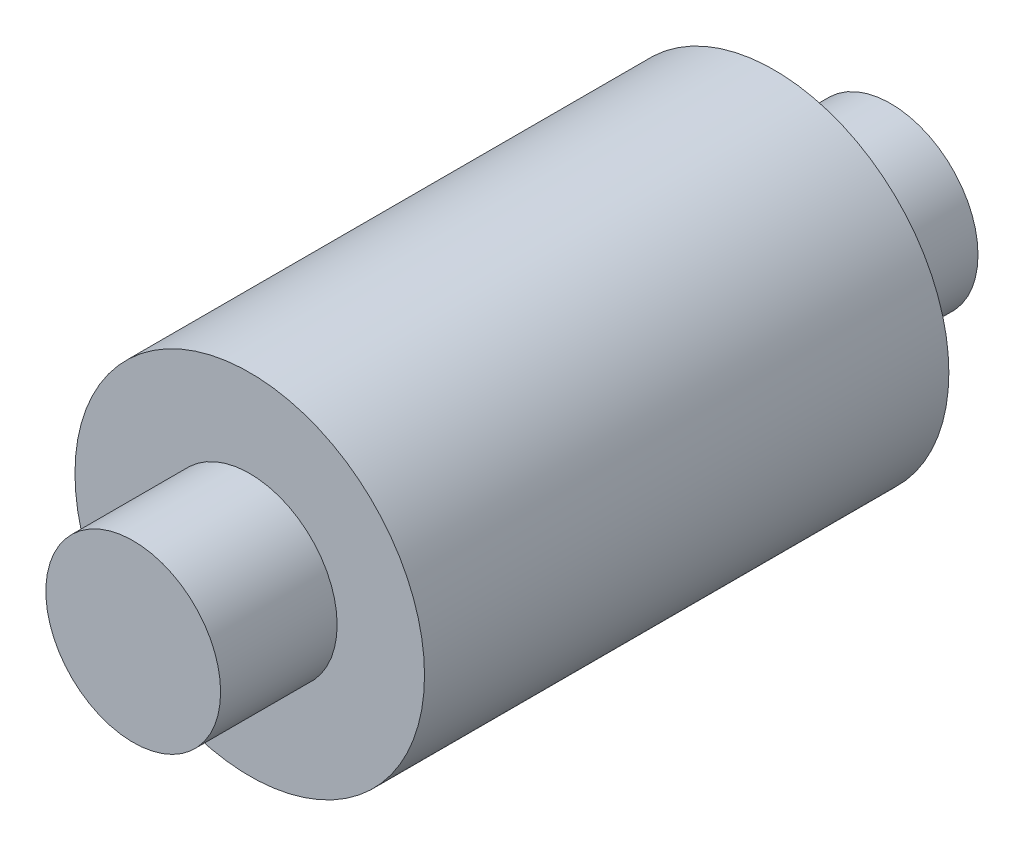
SolidWorks part; units mm, degrees
material "1023 Chapa de acero al carbono (SS)"
ref_plane "Alzado" through (0, 0, 0) normal (0, 0, 1) x (1, 0, 0)
ref_plane "Planta" through (0, 0, 0) normal (0, 1, 0) x (1, 0, 0)
ref_plane "Vista lateral" through (0, 0, 0) normal (1, 0, 0) x (0, 0, -1)
sketch "Croquis1" plane through (0, 0, 0) normal (1, 0, 0) x (0, 0, -1)
  line L0 (0, 0) -> (6.5, 0)
  line L1 (0, 0) -> (0, 0.75)
  line L2 (0, 0.75) -> (1, 0.75)
  line L3 (1, 0.75) -> (1, 1.5)
  line L4 (1, 1.5) -> (5.5, 1.5)
  line L5 (5.5, 1.5) -> (5.5, 0.75)
  line L6 (5.5, 0.75) -> (6.5, 0.75)
  line L7 (6.5, 0.75) -> (6.5, 0)
  point P9 (0.5, 0.75)
  dimension "D1" = 0.75
  dimension "D2" = 4.5
  dimension "D3" = 1
  dimension "D4" = 1
  dimension "D5" = 1.5
  dimension "D6" = 0.75
revolve "Revolución1" add sketch "Croquis1" angle 360 about L0
